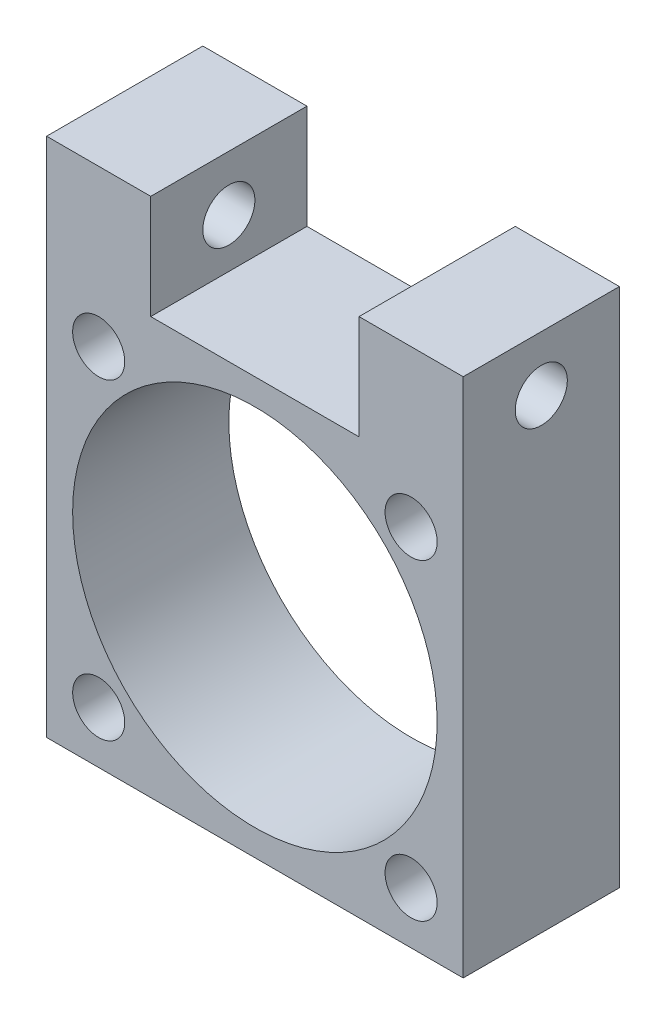
SolidWorks part; units mm, degrees
material "ABS"
ref_plane "Front Plane" through (0, 0, 0) normal (0, 0, 1) x (1, 0, 0)
ref_plane "Top Plane" through (0, 0, 0) normal (0, 1, 0) x (1, 0, 0)
ref_plane "Right Plane" through (0, 0, 0) normal (1, 0, 0) x (0, 0, -1)
sketch "Sketch1" plane through (0, 0, 0) normal (0, 0, 1) x (1, 0, 0)
  line L0 (0, 65.5134) -> (0, -91.6878) construction
  line L1 (-25.4, 25.4) -> (25.4, 25.4)
  line L2 (-25.4, 25.4) -> (-25.4, -25.4)
  line L3 (-25.4, -25.4) -> (25.4, -25.4)
  line L4 (25.4, 25.4) -> (25.4, -25.4)
  line L5 (77.439, 0) -> (-88.9, 0) construction
  dimension "D1" = 50.8
extrude "Boss-Extrude1" add sketch "Sketch1" along normal blind 19.05
sketch "Sketch2" plane through (0, 0, 0) normal (0, 0, -1) x (-1, 0, 0)
  circle A0 centre (0, 0) radius 22.225
  dimension "D1" = 44.45
extrude "Cut-Extrude1" cut sketch "Sketch2" against normal blind 25.4
ref_plane "Plane1" through (0, 0, 9.525) normal (0, 0, -1) x (-1, 0, 0)
sketch "Sketch3" plane through (-25.4, 0, 0) normal (-1, 0, 0) x (0, 0, 1)
  line L0 (19.05, 25.4) -> (0, 25.4) construction
  line L1 (0, 25.4) -> (19.05, 25.4)
  line L2 (0, 25.4) -> (0, 38.1)
  line L3 (0, 38.1) -> (19.05, 38.1)
  line L4 (19.05, 25.4) -> (19.05, 38.1)
  line L5 (9.525, 27.94) -> (9.525, -27.94) construction
  line L6 (9.525, 11.6872) -> (9.525, 51.0404) construction
  line L7 (19.05, 25.4) -> (19.05, -25.4) construction
  circle A0 centre (9.525, 31.3638) radius 3.175
  dimension "D3" = 6.35
  dimension "D2" = 12.7
extrude "Boss-Extrude2" add sketch "Sketch3" against normal blind 12.7
mirror "Mirror1" about plane through (0, 0, 0) normal (1, 0, 0) of "Boss-Extrude2"
sketch "Sketch4" plane through (0, 0, 0) normal (0, 0, -1) x (-1, 0, 0)
  line L0 (-25.4, -25.4) -> (-25.4, 38.1) construction
  line L2 (-12.7, 25.4) -> (12.7, 25.4) construction
  circle A0 centre (-19.05, 19.05) radius 3.175
  circle A1 centre (19.05, 19.05) radius 3.175
  circle A2 centre (19.05, -19.05) radius 3.175
  circle A3 centre (-19.05, -19.05) radius 3.175
  point P15 (0, 0)
  dimension "D1" = 6.35
  dimension "D2" = 6.35
  dimension "D3" = 6.35
  dimension "D4" = 4
extrude "Cut-Extrude2" cut sketch "Sketch4" against normal through all
